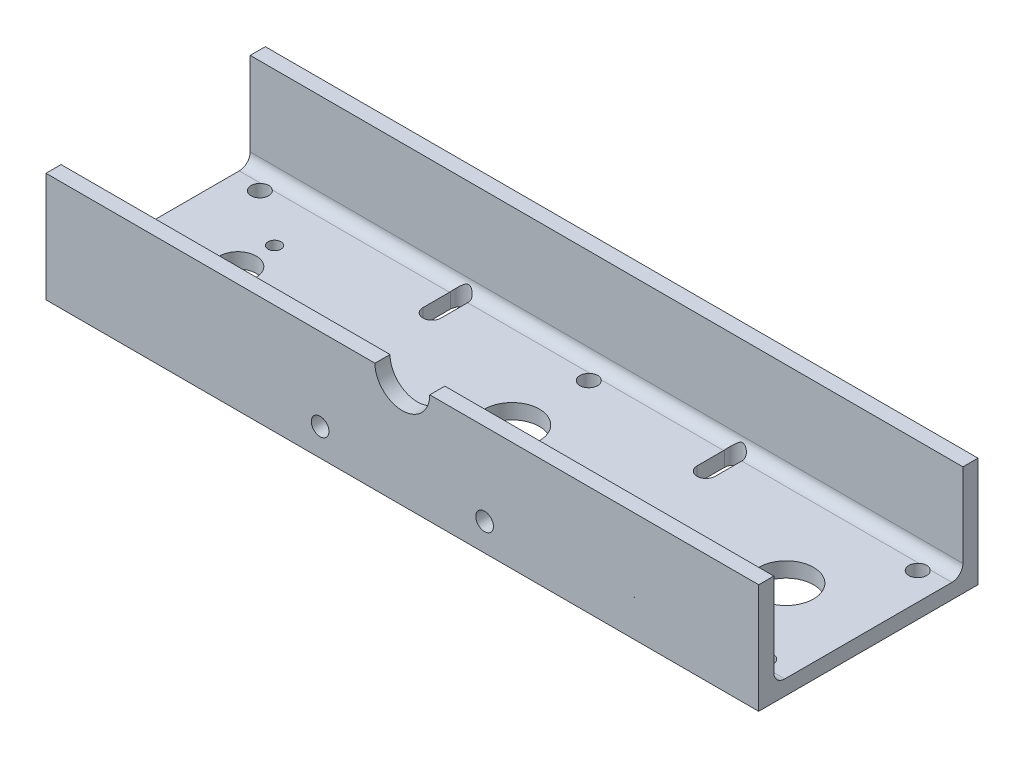
SolidWorks part; units mm, degrees
ref_plane "Front Plane" through (0, 0, 0) normal (0, 0, 1) x (1, 0, 0)
ref_plane "Top Plane" through (0, 0, 0) normal (0, 1, 0) x (1, 0, 0)
ref_plane "Right Plane" through (0, 0, 0) normal (1, 0, 0) x (0, 0, -1)
sketch "Sketch1" plane through (0, 0, 0) normal (1, 0, 0) x (0, 0, -1)
  line L0 (-21.9075, 9.2075) -> (21.9075, 9.2075)
  line L1 (-25.4, -12.7) -> (25.4, -12.7)
  line L2 (-25.4, -12.7) -> (-25.4, 12.7)
  line L3 (-25.4, 12.7) -> (25.4, 12.7)
  line L4 (25.4, -12.7) -> (25.4, 12.7)
  line L5 (-25.4, -12.7) -> (25.4, 12.7) construction
  line L6 (-25.4, 12.7) -> (25.4, -12.7) construction
  line L7 (21.9075, -6.6675) -> (21.9075, 9.2075)
  line L8 (-19.3675, -9.2075) -> (19.3675, -9.2075)
  line L9 (-21.9075, -6.6675) -> (-21.9075, 9.2075)
  line L10 (-21.9075, 9.2075) -> (-21.9075, 12.7)
  line L11 (21.9075, 9.2075) -> (21.9075, 12.7)
  line L12 (21.9075, -9.2075) -> (21.9075, 9.2075) construction
  line L13 (-21.9075, -9.2075) -> (21.9075, -9.2075) construction
  line L14 (-21.9075, -9.2075) -> (-21.9075, 9.2075) construction
  arc A0 (21.9075, -6.6675) -> (19.3675, -9.2075) centre (19.3675, -6.6675) cw
  arc A1 (-19.3675, -9.2075) -> (-21.9075, -6.6675) centre (-19.3675, -6.6675) cw
  point P0 (0, 0)
  dimension "D4" = 2.54
  dimension "D1" = 25.4
  dimension "D2" = 50.8
  dimension "D3" = 3.4925
extrude "Boss-Extrude1" add sketch "Sketch1" along normal blind 165.1 contours L8 A1 L9 L10 L3 L2 L1 L4 L11 L7 A0
sketch "Sketch2" plane through (0, -12.7, 0) normal (0, -1, 0) x (1, 0, 0)
  line L0 (0, 0) -> (165.1, 0) construction
  line L3 (0, 25.4) -> (0, -25.4) construction
  line L4 (165.1, 25.4) -> (165.1, -25.4) construction
  line L11 (0, 0) -> (19.05, 0)
  line L12 (165.1, 0) -> (146.05, 0)
  line L13 (19.05, 8.5) -> (19.05, -8.5) construction
  circle A4 centre (19.05, 0) radius 4.25
  circle A5 centre (146.05, 0) radius 6.35
  circle A6 centre (19.05, 8.5) radius 1.5
  circle A7 centre (19.05, -8.5) radius 1.5
  circle A8 centre (82.55, 0) radius 6.35
  dimension "D5" = 17
  dimension "D2" = 8.5
  dimension "D4" = 12.7
  dimension "D6" = 3
  dimension "D7" = 3
  dimension "D8" = 12.7
  dimension "D1" = 19.05
  dimension "D3" = 19.05
extrude "Cut-Extrude1" cut sketch "Sketch2" against normal blind 11.938
sketch "Sketch3" plane through (0, -12.7, 0) normal (0, -1, 0) x (1, 0, 0)
  line L0 (19.05, 0) -> (41.0012, 0) construction
  line L1 (41.0012, 0) -> (60.5988, 0) construction
  line L2 (50.8, 0) -> (50.8, 16.3974) construction
  line L3 (50.8, 19.5724) -> (50.8, 13.2224) construction
  line L4 (52.9, 19.5724) -> (52.9, 13.2224)
  line L5 (48.7, 19.5724) -> (48.7, 13.2224)
  line L6 (82.55, 0) -> (82.55, 25.4)
  line L7 (165.1, 25.4) -> (0, 25.4) construction
  line L8 (124.0988, 0) -> (104.5012, 0) construction
  line L9 (114.3, 0) -> (114.3, 16.3974) construction
  line L10 (114.3, 19.5724) -> (114.3, 13.2224) construction
  line L11 (112.2, 19.5724) -> (112.2, 13.2224)
  line L12 (116.4, 19.5724) -> (116.4, 13.2224)
  line L13 (114.3, -19.5724) -> (114.3, -13.2224) construction
  line L14 (112.2, -19.5724) -> (112.2, -13.2224)
  line L15 (116.4, -19.5724) -> (116.4, -13.2224)
  line L16 (50.8, -19.5724) -> (50.8, -13.2224) construction
  line L17 (52.9, -19.5724) -> (52.9, -13.2224)
  line L18 (48.7, -19.5724) -> (48.7, -13.2224)
  circle A0 centre (19.05, 0) radius 21.9512
  circle A1 centre (82.55, 0) radius 21.9512
  circle A2 centre (146.05, 0) radius 21.9512
  arc A3 (26.5015, 20.6477) -> (75.0985, 20.6477) centre (50.8, 87.9783) ccw construction
  circle A4 centre (50.8, 16.3974) radius 2.1
  arc A5 (52.9, 19.5724) -> (48.7, 19.5724) centre (50.8, 19.5724) ccw
  arc A6 (48.7, 13.2224) -> (52.9, 13.2224) centre (50.8, 13.2224) ccw
  arc A7 (138.5985, 20.6477) -> (90.0015, 20.6477) centre (114.3, 87.9783) cw construction
  arc A8 (112.2, 19.5724) -> (116.4, 19.5724) centre (114.3, 19.5724) cw
  arc A9 (116.4, 13.2224) -> (112.2, 13.2224) centre (114.3, 13.2224) cw
  arc A10 (112.2, -19.5724) -> (116.4, -19.5724) centre (114.3, -19.5724) ccw
  arc A11 (116.4, -13.2224) -> (112.2, -13.2224) centre (114.3, -13.2224) ccw
  arc A12 (52.9, -19.5724) -> (48.7, -19.5724) centre (50.8, -19.5724) cw
  arc A13 (48.7, -13.2224) -> (52.9, -13.2224) centre (50.8, -13.2224) cw
  point P16 (50.8, 16.3974)
  point P33 (114.3, 16.3974)
  point P40 (114.3, -16.3974)
  point P47 (50.8, -16.3974)
  dimension "D1" = 43.9023
  dimension "D2" = 43.9023
  dimension "D3" = 4.2
  dimension "D4" = 2.1
  dimension "D5" = 6.35
extrude "Cut-Extrude2" cut sketch "Sketch3" against normal blind 7.874 contours L4 A5 L5 A4 | A4 | L5 A6 L4 A4 | A9 L12 A8 L11 | L17 A13 L18 A12 | L14 A11 L15 A10
sketch "Sketch4" plane through (0, 0, 25.4) normal (0, 0, 1) x (1, 0, 0)
  line L4 (75.55, -26.1798) -> (89.4844, -26.1798)
  line L5 (89.4844, -23.8176) -> (75.55, -23.8176)
  line L6 (75.6156, -26.1798) -> (89.55, -26.1798)
  line L7 (89.55, -23.8176) -> (75.6156, -23.8176)
  line L8 (82.5172, -23.8176) -> (82.55, 38.1)
  circle A0 centre (82.55, 12.7) radius 6.35
  point P12 (82.55, 12.7)
  line M5 (165.1, 12.7) -> (0, 12.7)
  dimension "D1" = 12.7
extrude "Cut-Extrude3" cut sketch "Sketch4" against normal blind 12.446 contours L8 A0 M5 | A0 L8 M5
sketch "Sketch5" plane through (0, -12.7, 0) normal (0, -1, 0) x (1, 0, 0)
  line L0 (0, 25.4) -> (0, -25.4) construction
  line L1 (0, 25.4) -> (6.35, 25.4) construction
  line L2 (0, 25.4) -> (0, 17.78) construction
  line L3 (0, 17.78) -> (6.35, 17.78) construction
  line L4 (6.35, 25.4) -> (6.35, 17.78) construction
  line L5 (165.1, 25.4) -> (0, 25.4) construction
  circle A0 centre (6.35, 17.78) radius 2.05
  circle A1 centre (6.35, -17.78) radius 2.05
  circle A2 centre (82.55, -17.78) radius 2.05
  circle A3 centre (158.75, -17.78) radius 2.05
  circle A4 centre (82.55, 17.78) radius 2.05
  circle A5 centre (158.75, 17.78) radius 2.05
  dimension "D3" = 4.1
  dimension "D1" = 7.62
  dimension "D2" = 6.35
  dimension "D4" = 2
  dimension "D5" = 3
extrude "Cut-Extrude4" cut sketch "Sketch5" against normal blind 6.35
sketch "Sketch6" plane through (0, 0, 25.4) normal (0, 0, 1) x (1, 0, 0)
  circle A2 centre (101.6, -6.35) radius 2.05
  circle A3 centre (63.5, -6.35) radius 2.05
extrude "Cut-Extrude5" cut sketch "Sketch6" against normal blind 6.35
